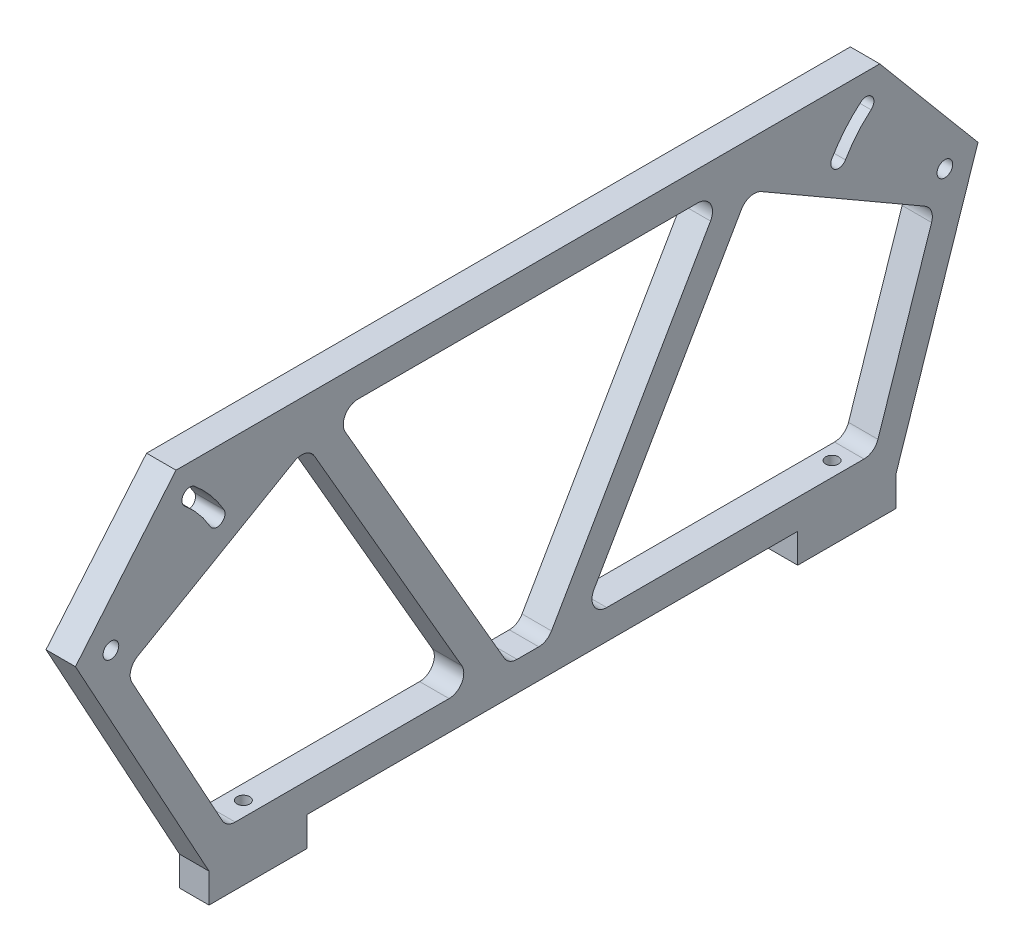
SolidWorks part; units mm, degrees
ref_plane "Front Plane" through (0, 0, 0) normal (0, 0, 1) x (1, 0, 0)
ref_plane "Top Plane" through (0, 0, 0) normal (0, 1, 0) x (1, 0, 0)
ref_plane "Right Plane" through (0, 0, 0) normal (1, 0, 0) x (0, 0, -1)
sketch "Sketch1" plane through (0, 0, 0) normal (1, 0, 0) x (0, 0, -1)
  line L0 (-65, 0) -> (-45, 0)
  line L1 (-45, 0) -> (-45, 6)
  line L2 (-65, 0) -> (-65, 6)
  line L3 (55, 0) -> (75, 0)
  line L4 (75, 0) -> (75, 6)
  line L5 (55, 0) -> (55, 6)
  line L6 (-85, 55) -> (-65.8489, 71.0697) construction
  line L7 (65.8489, 71.0697) -> (85, 55) construction
  line L8 (-68.9303, 74.1511) -> (-85, 55) construction
  line L9 (-85, 55) -> (-63.3494, 67.5) construction
  line L10 (63.3494, 67.5) -> (85, 55) construction
  line L11 (85, 55) -> (68.9303, 74.1511) construction
  line L12 (-65, 6) -> (-92.2327, 55.7147)
  line L13 (-92.2327, 55.7147) -> (-71.7282, 80.1511)
  line L14 (-71.7282, 80.1511) -> (71.7282, 80.1511)
  line L15 (71.7282, 80.1511) -> (91.7528, 56.2866)
  line L16 (91.7528, 56.2866) -> (75, 6)
  line L17 (55, 6) -> (-45, 6)
  line L18 (-82.1167, 49.7365) -> (-45.0255, 71.1511)
  line L19 (-39.8293, 74.1511) -> (39.8293, 74.1511)
  line L20 (45.0255, 71.1511) -> (83.0642, 49.1894)
  line L21 (83.0642, 49.1894) -> (70.6747, 12)
  line L22 (70.6747, 12) -> (10.8745, 12)
  line L23 (10.8745, 12) -> (45.0255, 71.1511)
  line L25 (39.8293, 74.1511) -> (3.9463, 12)
  line L26 (3.9463, 12) -> (-3.9463, 12)
  line L27 (-3.9463, 12) -> (-39.8293, 74.1511)
  line L29 (-45.0255, 71.1511) -> (-10.8745, 12)
  line L30 (-10.8745, 12) -> (-61.4455, 12)
  line L31 (-61.4455, 12) -> (-82.1167, 49.7365)
  circle A0 centre (-85, 55) radius 1.6
  circle A1 centre (85, 55) radius 1.6
  arc A2 (-68.9303, 74.1511) -> (-63.3494, 67.5) centre (-85, 55) cw construction
  arc A3 (-61.9637, 68.3) -> (-67.9018, 75.3768) centre (-85, 55) ccw
  arc A4 (-64.735, 66.7) -> (-69.9588, 72.9254) centre (-85, 55) ccw
  arc A5 (-64.735, 66.7) -> (-61.9637, 68.3) centre (-63.3494, 67.5) ccw
  arc A6 (-67.9018, 75.3768) -> (-69.9588, 72.9254) centre (-68.9303, 74.1511) ccw
  arc A7 (63.3494, 67.5) -> (68.9303, 74.1511) centre (85, 55) cw construction
  arc A8 (67.9018, 75.3768) -> (61.9637, 68.3) centre (85, 55) ccw
  arc A9 (69.9588, 72.9254) -> (64.735, 66.7) centre (85, 55) ccw
  arc A10 (69.9588, 72.9254) -> (67.9018, 75.3768) centre (68.9303, 74.1511) ccw
  arc A11 (61.9637, 68.3) -> (64.735, 66.7) centre (63.3494, 67.5) ccw
  point P18 (-65.8489, 71.0697)
  point P28 (65.8489, 71.0697)
  dimension "D11" = 3.2
  dimension "D12" = 1.6
  dimension "D1" = 6
  dimension "D2" = 20
  dimension "D3" = 45
  dimension "D4" = 100
  dimension "D5" = 25
  dimension "D6" = 40
  dimension "D7" = 40
  dimension "D8" = 85
  dimension "D9" = 85
  dimension "D10" = 55
  dimension "D13" = 10
  dimension "D14" = 10
  dimension "D15" = 6
  dimension "D16" = 6
  dimension "D17" = 6
  dimension "D18" = 6
  dimension "D19" = 6
  dimension "D20" = 6
  dimension "D21" = 6
  dimension "D22" = 6
  dimension "D23" = 6
  dimension "D24" = 6
  dimension "D25" = 6
  dimension "D26" = 6
  dimension "D27" = 6
  dimension "D28" = 60
  dimension "D29" = 60
extrude "Boss-Extrude1" add sketch "Sketch1" along normal blind 6
fillet "Fillet1" radius 3 12 edges at (3, 12, -70.6747) (3, 49.1894, -83.0642) (3, 71.1511, -45.0255) (3, 12, -10.8745) (3, 12, 3.9463) (3, 12, -3.9463) (3, 12, 10.8745) (3, 12, 61.4455) (3, 74.1511, -39.8293) (3, 74.1511, 39.8293) (3, 49.7365, 82.1167) (3, 71.1511, 45.0255)
sketch "Sketch2" plane through (0, 0, 0) normal (0, -1, 0) x (1, 0, 0)
  line L0 (6, -55) -> (6, -75) construction
  line L1 (6, -75) -> (0, -75) construction
  line L2 (6, 65) -> (0, 65) construction
  circle A0 centre (3, 55) radius 1.3
  circle A1 centre (3, -65) radius 1.3
  dimension "D1" = 2.6
  dimension "D2" = 3
  dimension "D3" = 10
  dimension "D4" = 10
extrude "Cut-Extrude1" cut sketch "Sketch2" against normal up to next
